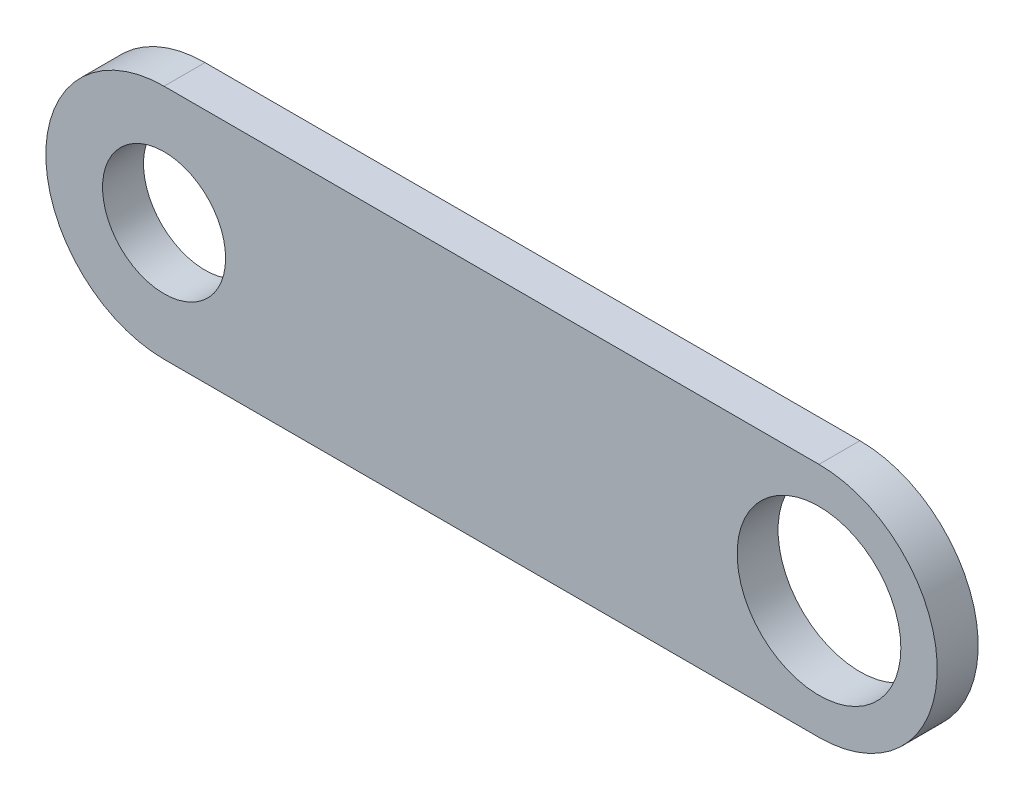
SolidWorks part; units mm, degrees
ref_plane "Front Plane" through (0, 0, 0) normal (0, 0, 1) x (1, 0, 0)
ref_plane "Top Plane" through (0, 0, 0) normal (0, 1, 0) x (1, 0, 0)
ref_plane "Right Plane" through (0, 0, 0) normal (1, 0, 0) x (0, 0, -1)
sketch "Sketch1" plane through (0, 0, 0) normal (0, 0, 1) x (1, 0, 0)
  line L0 (-50.8, 0) -> (50.8, 0) construction
  line L1 (-50.8, 18.3444) -> (50.8, 18.3444)
  line L2 (-50.8, -18.3444) -> (50.8, -18.3444)
  arc A0 (-50.8, 18.3444) -> (-50.8, -18.3444) centre (-50.8, 0) ccw
  arc A1 (50.8, -18.3444) -> (50.8, 18.3444) centre (50.8, 0) ccw
  circle A2 centre (-50.8, 0) radius 9.544
  circle A3 centre (50.8, 0) radius 12.7
  point P2 (0, 0)
  dimension "D1" = 19.0881
  dimension "D2" = 25.4
  dimension "D4" = 18.3444
  dimension "D3" = 36.6889
  dimension "D5" = 101.6
extrude "Boss-Extrude1" add sketch "Sketch1" along normal mid plane 6.35 contours L2 A1 L1 A0 | A3 | A2
equation "\"d_upper_shaft\"= 0.7515"
equation "\"d_lower_shaft\"= 1"
equation "\"t\"= 0.25"
equation "\"l\"= 4"
equation "\"force\"= 1000"
equation "\"stress_allowable\"= 9000"
equation "\"area\"= \"force\" / \"stress_allowable\""
equation "\"width\"= ( \"area\" / \"t\" ) + \"d_lower_shaft\""
equation "\"D1@Sketch1\"=\"d_upper_shaft\""
equation "\"D2@Sketch1\"=\"d_lower_shaft\""
equation "\"D3@Sketch1\"=\"width\""
equation "\"D5@Sketch1\"=\"l\""
equation "\"D1@Boss-Extrude1\"=\"t\""
